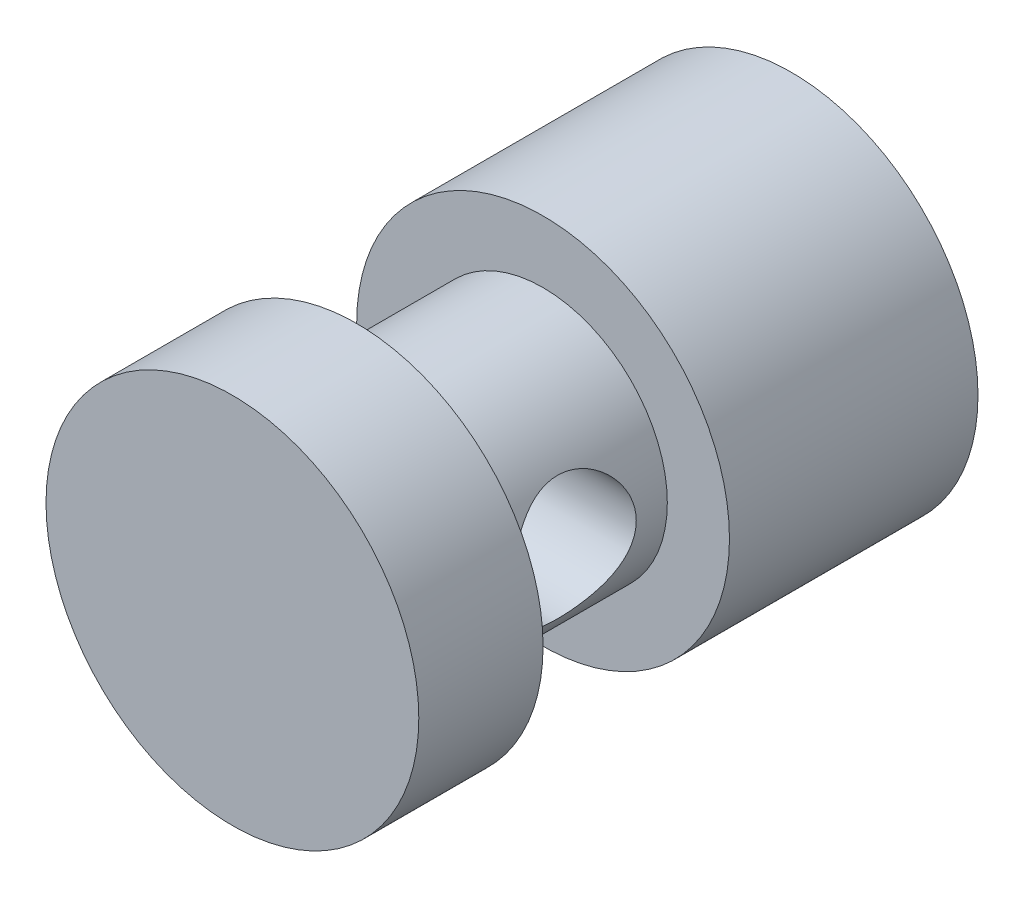
SolidWorks part; units mm, degrees
ref_plane "前视基准面" through (0, 0, 0) normal (0, 0, 1) x (1, 0, 0)
ref_plane "上视基准面" through (0, 0, 0) normal (0, 1, 0) x (1, 0, 0)
ref_plane "右视基准面" through (0, 0, 0) normal (1, 0, 0) x (0, 0, -1)
other "Configuration Table"
sketch "草图2" plane through (0, 0, 0) normal (0, 0, 1) x (1, 0, 0)
  circle A0 centre (0, 0) radius 3
  dimension "D1" = 6
extrude "凸台-拉伸1" add sketch "草图2" along normal blind 4
sketch "草图3" plane through (0, 0, 4) normal (0, 0, 1) x (1, 0, 0)
  circle A0 centre (0, 0) radius 2
  dimension "D1" = 4
extrude "凸台-拉伸2" add sketch "草图3" along normal blind 3
ref_plane "基准面1" through (2, 0, 0) normal (1, 0, 0) x (0, 0, -1)
sketch "草图4" plane through (2, 0, 0) normal (1, 0, 0) x (0, 0, -1)
  line L0 (-5.5, 2) -> (-5.5, -2) construction
  line L1 (-4, 2) -> (-7, 2) construction
  line L2 (-7, -2) -> (-4, -2) construction
  circle A0 centre (-5.5, 0) radius 1
  dimension "D1" = 2
extrude "切除-拉伸1" cut sketch "草图4" against normal through all
sketch "草图5" plane through (0, 0, 7) normal (0, 0, 1) x (1, 0, 0)
  circle A0 centre (0, 0) radius 3
extrude "凸台-拉伸3" add sketch "草图5" along normal blind 2
